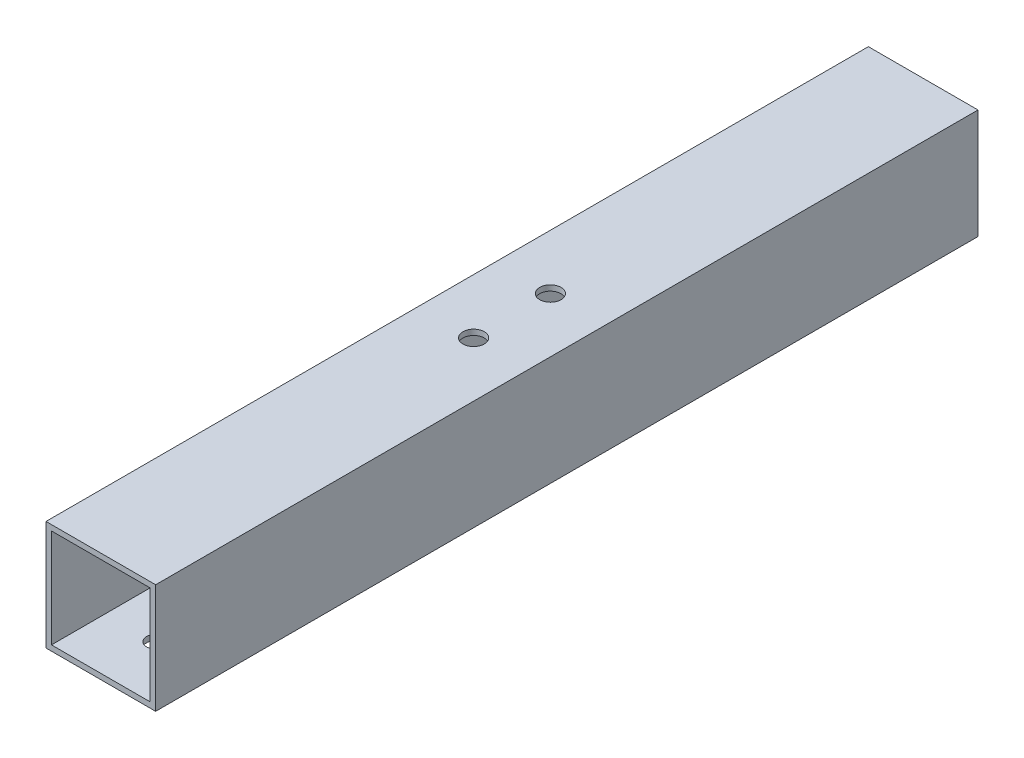
SolidWorks part; units mm, degrees
material "1060 合金"
ref_plane "前视基准面" through (0, 0, 0) normal (0, 0, 1) x (1, 0, 0)
ref_plane "上视基准面" through (0, 0, 0) normal (0, 1, 0) x (1, 0, 0)
ref_plane "右视基准面" through (0, 0, 0) normal (1, 0, 0) x (0, 0, -1)
other "Configuration Table"
sketch "草图1" plane through (0, 0, 0) normal (0, 0, 1) x (1, 0, 0)
  line L1 (0, 0) -> (20, 0)
  line L2 (0, 0) -> (0, -20)
  line L3 (0, -20) -> (20, -20)
  line L4 (20, 0) -> (20, -20)
  dimension "D1" = 20
  dimension "D2" = 20
extrude "拉伸-薄壁1" add sketch "草图1" along normal blind 150 thin
sketch "草图2" plane through (0, -20, 0) normal (0, -1, 0) x (1, 0, 0)
  circle A1 centre (7.5, 825) radius 2.6
  circle A2 centre (7.5, 825) radius 2.6
  dimension "D1" = 0
extrude "切除-拉伸1" [suppressed] cut sketch "草图2" against normal up to next
sketch "草图3" plane through (0, -20, 0) normal (0, -1, 0) x (1, 0, 0)
  line L0 (20, 150) -> (20, 0) construction
  line L3 (0, 0) -> (20, 0) construction
  circle A0 centre (10, 82) radius 1.95
  circle A1 centre (10, 68) radius 1.95
  dimension "D1" = 3.9
  dimension "D4" = 3.9
  dimension "D2" = 10
  dimension "D3" = 14
  dimension "D5" = 68
  dimension "D6" = 10
extrude "切除-拉伸2" cut sketch "草图3" against normal through all
sketch "草图4" plane through (0, -20, 0) normal (0, -1, 0) x (1, 0, 0)
  line L0 (0, 150) -> (20, 150) construction
  line L1 (0, 150) -> (0, 0) construction
  circle A0 centre (10, 140) radius 1.65
  circle A1 centre (10, 10) radius 1.65
  dimension "D2" = 3.3
  dimension "D1" = 10
  dimension "D3" = 10
  dimension "D4" = 2
extrude "切除-拉伸3" cut sketch "草图4" against normal up to next
